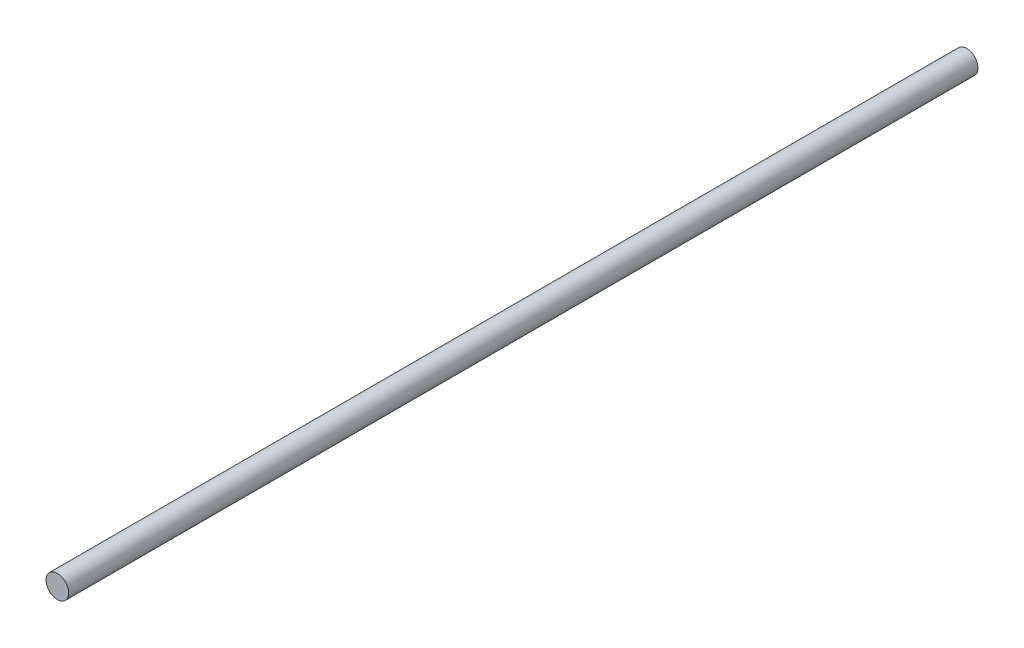
SolidWorks part; units mm, degrees
ref_plane "Front Plane" through (0, 0, 0) normal (0, 0, 1) x (1, 0, 0)
ref_plane "Top Plane" through (0, 0, 0) normal (0, 1, 0) x (1, 0, 0)
ref_plane "Right Plane" through (0, 0, 0) normal (1, 0, 0) x (0, 0, -1)
sketch "Sketch1" plane through (0, 0, 0) normal (0, 0, 1) x (1, 0, 0)
  circle A0 centre (0, 0) radius 0.5
  dimension "D1" = 1
extrude "Boss-Extrude1" add sketch "Sketch1" along normal blind 40
